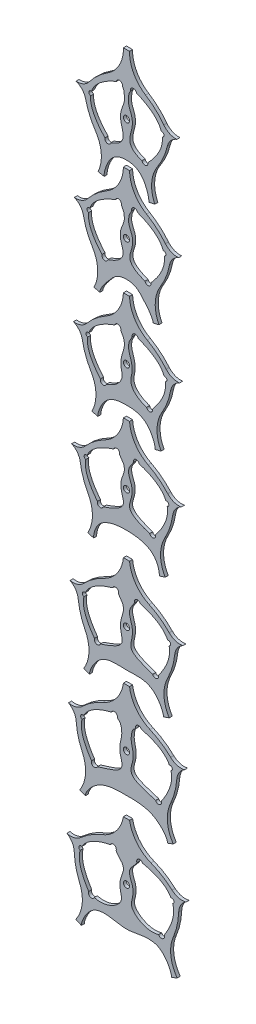
SolidWorks part; units mm, degrees
ref_plane "Front Plane" through (0, 0, 0) normal (0, 0, 1) x (1, 0, 0)
ref_plane "Top Plane" through (0, 0, 0) normal (0, 1, 0) x (1, 0, 0)
ref_plane "Right Plane" through (0, 0, 0) normal (1, 0, 0) x (0, 0, -1)
sketch "Sketch1" plane through (0, 0, 0) normal (0, 0, 1) x (1, 0, 0)
  line L0 (112.8027, 2.1803) -> (107.8321, 1.1314)
  line L1 (86.7726, 101.4585) -> (91.8526, 101.4585)
  line L2 (118.2938, 57.0694) -> (118.2268, 57.0566)
  line L3 (91.8526, 101.4585) -> (112.8027, 2.1803) construction
  line L4 (92.6064, 73.4013) -> (97.5769, 74.4502) construction
  line L5 (102.1555, 28.1498) -> (107.1261, 29.1987) construction
  line L6 (91.8526, 15.9076) -> (116.2488, -82.5805) construction
  line L7 (104.7033, -56.9977) -> (109.6343, -55.7762) construction
  line L8 (116.2488, -82.5805) -> (111.3178, -83.8019)
  line L9 (89.3126, 15.9076) -> (89.3126, -63.4628) construction
  line L10 (93.5834, -12.1064) -> (98.5144, -10.8849) construction
  line L11 (89.3126, 101.4585) -> (89.3126, 22.0881) construction
  line L12 (119.8242, -27.5334) -> (119.7577, -27.5485)
  line L13 (86.7726, 15.9076) -> (91.8526, 15.9076)
  line L14 (91.8526, -74.3544) -> (117.9639, -172.4017) construction
  line L15 (105.9737, -147.0243) -> (110.8826, -145.717) construction
  line L16 (117.9639, -172.4017) -> (113.055, -173.709)
  line L17 (89.3126, -74.3544) -> (89.3126, -153.7248) construction
  line L18 (94.0721, -102.3339) -> (98.981, -101.0266) construction
  line L19 (120.5781, -117.3006) -> (120.5119, -117.3169)
  line L20 (86.7726, -74.3544) -> (91.8526, -74.3544)
  line L21 (91.8526, -164.1408) -> (121.364, -261.2188) construction
  line L22 (108.497, -236.2745) -> (113.3573, -234.797) construction
  line L23 (121.364, -261.2188) -> (116.5036, -262.6963)
  line L24 (89.3126, -164.1408) -> (89.3126, -243.5112) construction
  line L25 (95.0455, -192.0259) -> (99.9059, -190.5484) construction
  line L26 (122.0569, -206.0601) -> (121.9913, -206.0787)
  line L27 (86.7726, -164.1408) -> (91.8526, -164.1408)
  line L28 (91.8526, -264.4679) -> (124.7283, -360.4588) construction
  line L29 (111, -335.978) -> (115.8059, -334.332) construction
  line L30 (124.7283, -360.4588) -> (119.9223, -362.1048)
  line L31 (89.3126, -264.4679) -> (89.3126, -343.8383) construction
  line L32 (96.0151, -292.2248) -> (100.821, -290.5789) construction
  line L33 (123.499, -305.3094) -> (123.4341, -305.3303)
  line L34 (86.7726, -264.4679) -> (91.8526, -264.4679)
  line L35 (91.8526, -354.4743) -> (128.0583, -449.2594) construction
  line L36 (113.484, -425.2726) -> (118.2296, -423.4599) construction
  line L37 (128.0583, -449.2594) -> (123.3127, -451.0721)
  line L38 (89.3126, -354.4743) -> (89.3126, -433.8447) construction
  line L39 (96.9813, -382.0691) -> (101.7268, -380.2564) construction
  line L40 (124.9051, -394.1865) -> (124.841, -394.2096)
  line L41 (86.7726, -354.4743) -> (91.8526, -354.4743)
  line L42 (91.8526, -450.3479) -> (131.3498, -543.8093) construction
  line L43 (115.9458, -520.3466) -> (120.6251, -518.3692) construction
  line L44 (131.3498, -543.8093) -> (126.6704, -545.7868)
  line L45 (89.3126, -450.3479) -> (89.3126, -529.7183) construction
  line L46 (97.9428, -477.7465) -> (102.6221, -475.769) construction
  line L47 (126.2732, -488.8803) -> (126.2099, -488.9057)
  line L48 (86.7726, -450.3479) -> (91.8526, -450.3479)
  line L49 (80.6823, -477.7465) -> (76.003, -475.769) construction
  line L50 (62.6793, -520.3466) -> (58, -518.3692) construction
  line L51 (86.7726, -450.3479) -> (47.2754, -543.8093) construction
  line L52 (81.6439, -382.0691) -> (76.8983, -380.2564) construction
  line L53 (65.1411, -425.2726) -> (60.3956, -423.4599) construction
  line L54 (86.7726, -354.4743) -> (50.5669, -449.2594) construction
  line L55 (82.61, -292.2248) -> (77.8041, -290.5789) construction
  line L56 (67.6251, -335.978) -> (62.8192, -334.332) construction
  line L57 (86.7726, -264.4679) -> (53.8969, -360.4588) construction
  line L58 (83.5796, -192.0259) -> (78.7192, -190.5484) construction
  line L59 (70.1282, -236.2745) -> (65.2678, -234.797) construction
  line L60 (86.7726, -164.1408) -> (57.2611, -261.2188) construction
  line L61 (84.5531, -102.3339) -> (79.6442, -101.0266) construction
  line L62 (72.6514, -147.0243) -> (67.7425, -145.717) construction
  line L63 (86.7726, -74.3544) -> (60.6612, -172.4017) construction
  line L64 (85.0417, -12.1064) -> (80.1107, -10.8849) construction
  line L65 (73.9218, -56.9977) -> (68.9908, -55.7762) construction
  line L66 (86.7726, 15.9076) -> (62.3764, -82.5805) construction
  line L67 (76.4696, 28.1498) -> (71.4991, 29.1987) construction
  line L68 (86.0188, 73.4013) -> (81.0482, 74.4502) construction
  line L69 (86.7726, 101.4585) -> (65.8225, 2.1803) construction
  line L70 (52.3519, -488.8803) -> (52.4152, -488.9057)
  line L71 (47.2754, -543.8093) -> (51.9547, -545.7868)
  line L72 (53.72, -394.1865) -> (53.7842, -394.2096)
  line L73 (50.5669, -449.2594) -> (55.3124, -451.0721)
  line L74 (55.1261, -305.3094) -> (55.191, -305.3303)
  line L75 (53.8969, -360.4588) -> (58.7028, -362.1048)
  line L76 (56.5682, -206.0601) -> (56.6338, -206.0787)
  line L77 (57.2611, -261.2188) -> (62.1215, -262.6963)
  line L78 (58.047, -117.3006) -> (58.1132, -117.3169)
  line L79 (60.6612, -172.4017) -> (65.5701, -173.709)
  line L80 (58.8009, -27.5334) -> (58.8674, -27.5485)
  line L81 (62.3764, -82.5805) -> (67.3073, -83.8019)
  line L82 (60.3314, 57.0694) -> (60.3983, 57.0566)
  line L83 (65.8225, 2.1803) -> (70.793, 1.1314)
  arc A0 (97.5769, 74.4502) -> (92.6064, 73.4013) centre (95.0916, 73.9257) ccw
  arc A1 (107.1261, 29.1987) -> (102.1555, 28.1498) centre (104.6408, 28.6742) cw
  circle A2 centre (89.3126, 51.5463) radius 2.54
  circle A3 centre (89.3126, -34.0046) radius 2.54
  arc A4 (109.6343, -55.7762) -> (104.7033, -56.9977) centre (107.1688, -56.387) cw
  arc A5 (98.5144, -10.8849) -> (93.5834, -12.1064) centre (96.0489, -11.4957) ccw
  circle A6 centre (89.3126, -124.2666) radius 2.54
  arc A7 (110.8826, -145.717) -> (105.9737, -147.0243) centre (108.4282, -146.3706) cw
  arc A8 (98.981, -101.0266) -> (94.0721, -102.3339) centre (96.5265, -101.6802) ccw
  circle A9 centre (89.3126, -214.0529) radius 2.54
  arc A10 (113.3573, -234.797) -> (108.497, -236.2745) centre (110.9272, -235.5358) cw
  arc A11 (99.9059, -190.5484) -> (95.0455, -192.0259) centre (97.4757, -191.2871) ccw
  circle A12 centre (89.3126, -312.7279) radius 2.54
  arc A13 (115.8059, -334.332) -> (111, -335.978) centre (113.403, -335.155) cw
  arc A14 (100.821, -290.5789) -> (96.0151, -292.2248) centre (98.4181, -291.4019) ccw
  circle A15 centre (89.3126, -401.8464) radius 2.54
  arc A16 (118.2296, -423.4599) -> (113.484, -425.2726) centre (115.8568, -424.3662) cw
  arc A17 (101.7268, -380.2564) -> (96.9813, -382.0691) centre (99.3541, -381.1627) ccw
  circle A18 centre (89.3126, -497.72) radius 2.54
  arc A19 (120.6251, -518.3692) -> (115.9458, -520.3466) centre (118.2855, -519.3579) cw
  arc A20 (102.6221, -475.769) -> (97.9428, -477.7465) centre (100.2825, -476.7577) ccw
  arc A21 (76.003, -475.769) -> (80.6823, -477.7465) centre (78.3427, -476.7577) cw
  arc A22 (58, -518.3692) -> (62.6793, -520.3466) centre (60.3397, -519.3579) ccw
  arc A23 (76.8983, -380.2564) -> (81.6439, -382.0691) centre (79.2711, -381.1627) cw
  arc A24 (60.3956, -423.4599) -> (65.1411, -425.2726) centre (62.7684, -424.3662) ccw
  arc A25 (77.8041, -290.5789) -> (82.61, -292.2248) centre (80.2071, -291.4019) cw
  arc A26 (62.8192, -334.332) -> (67.6251, -335.978) centre (65.2222, -335.155) ccw
  arc A27 (78.7192, -190.5484) -> (83.5796, -192.0259) centre (81.1494, -191.2871) cw
  arc A28 (65.2678, -234.797) -> (70.1282, -236.2745) centre (67.698, -235.5358) ccw
  arc A29 (79.6442, -101.0266) -> (84.5531, -102.3339) centre (82.0986, -101.6802) cw
  arc A30 (67.7425, -145.717) -> (72.6514, -147.0243) centre (70.1969, -146.3706) ccw
  arc A31 (80.1107, -10.8849) -> (85.0417, -12.1064) centre (82.5762, -11.4957) cw
  arc A32 (68.9908, -55.7762) -> (73.9218, -56.9977) centre (71.4563, -56.387) ccw
  arc A33 (71.4991, 29.1987) -> (76.4696, 28.1498) centre (73.9843, 28.6742) ccw
  arc A34 (81.0482, 74.4502) -> (86.0188, 73.4013) centre (83.5335, 73.9257) cw
  spline S0 degree 3 poles (92.6064, 73.4013) (90.7172, 69.8758) (91.4007, 69.3427) (90.6032, 59.9362) (96.814, 54.676) (90.7892, 37.3434) (93.5122, 31.002) (102.1555, 28.1498) knots 0 0 0 0 0.293254 0.369172 0.759179 0.846962 1 1 1 1
  spline S1 degree 3 poles (107.8321, 1.1314) (108.105, 3.9211) (104.5336, 16.6488) (96.4099, 22.2747) (89.3126, 22.0881) knots 0 0 0 0 0.457136 1 1 1 1
  spline S2 degree 3 poles (93.5834, -12.1064) (91.6943, -15.6318) (91.3365, -16.2096) (90.6706, -25.6141) (97.4795, -30.7687) (90.1705, -48.3057) (96.06, -54.1455) (104.7033, -56.9977) knots 0 0 0 0 0.293254 0.369172 0.759179 0.846962 1 1 1 1
  spline S3 degree 3 poles (111.3178, -83.8019) (111.5906, -81.0122) (102.464, -69.2688) (96.4099, -63.2763) (89.3126, -63.4628) knots 0 0 0 0 0.457136 1 1 1 1
  spline S4 degree 3 poles (94.0721, -102.3339) (92.1829, -105.8593) (91.2696, -106.5128) (90.7601, -115.8113) (95.9971, -123.0387) (91.5348, -136.7164) (97.3305, -144.1721) (105.9737, -147.0243) knots 0 0 0 0 0.293254 0.369172 0.759179 0.846962 1 1 1 1
  spline S5 degree 3 poles (113.055, -173.709) (113.3278, -170.9193) (107.9556, -156.16) (96.4099, -153.5383) (89.3126, -153.7248) knots 0 0 0 0 0.457136 1 1 1 1
  spline S6 degree 3 poles (95.0455, -192.0259) (93.1564, -195.5514) (91.208, -196.2555) (90.8234, -205.671) (96.7865, -210.1618) (89.6133, -228.6395) (99.8537, -233.4224) (108.497, -236.2745) knots 0 0 0 0 0.293254 0.369172 0.759179 0.846962 1 1 1 1
  spline S7 degree 3 poles (116.5036, -262.6963) (116.7765, -259.9066) (113.5664, -245.8994) (96.4099, -243.3246) (89.3126, -243.5112) knots 0 0 0 0 0.457136 1 1 1 1
  spline S8 degree 3 poles (96.0151, -292.2248) (94.126, -295.7503) (91.9511, -296.9994) (91.6538, -306.3232) (96.459, -311.0004) (91.0565, -328.7947) (102.3567, -333.1258) (111, -335.978) knots 0 0 0 0 0.293254 0.369172 0.759179 0.846962 1 1 1 1
  spline S9 degree 3 poles (119.9223, -362.1048) (120.1952, -359.3151) (111.6832, -341.6533) (96.4099, -343.6517) (89.3126, -343.8383) knots 0 0 0 0 0.457136 1 1 1 1
  spline S10 degree 3 poles (96.9813, -382.0691) (94.2417, -383.3935) (93.4077, -386.9113) (92.9499, -395.2796) (96.3902, -401.2054) (93.0624, -411.2622) (92.3782, -419.5654) (104.8407, -422.4204) (113.484, -425.2726) knots 0 0 0 0 0.280226 0.352772 0.684044 0.73546 0.825529 1 1 1 1
  spline S11 degree 3 poles (123.3127, -451.0721) (123.5855, -448.2824) (113.3022, -433.8997) (96.4099, -433.6581) (89.3126, -433.8447) knots 0 0 0 0 0.457136 1 1 1 1
  spline S12 degree 3 poles (97.9428, -477.7465) (96.0537, -481.2719) (91.8104, -483.5573) (91.8093, -492.7348) (97.0417, -497.1538) (91.4592, -514.3324) (106.7575, -523.1596) (115.9458, -520.3466) knots 0 0 0 0 0.293254 0.369172 0.759179 0.846962 1 1 1 1
  spline S13 degree 3 poles (126.6704, -545.7868) (126.9433, -542.9971) (117.5696, -521.1447) (96.5803, -529.8343) (89.3126, -529.7183) knots 0 0 0 0 0.457136 1 1 1 1
  spline S14 degree 3 poles (51.9547, -545.7868) (51.6818, -542.9971) (61.0556, -521.1447) (82.0448, -529.8343) (89.3126, -529.7183) knots 0 0 0 0 0.457136 1 1 1 1
  spline S15 degree 3 poles (80.6823, -477.7465) (82.5714, -481.2719) (86.8147, -483.5573) (86.8159, -492.7348) (81.5834, -497.1538) (87.1659, -514.3324) (71.8676, -523.1596) (62.6793, -520.3466) knots 0 0 0 0 0.293254 0.369172 0.759179 0.846962 1 1 1 1
  spline S16 degree 3 poles (55.3124, -451.0721) (55.0396, -448.2824) (65.323, -433.8997) (82.2152, -433.6581) (89.3126, -433.8447) knots 0 0 0 0 0.457136 1 1 1 1
  spline S17 degree 3 poles (81.6439, -382.0691) (84.3834, -383.3935) (85.2174, -386.9113) (85.6752, -395.2796) (82.2349, -401.2054) (85.5628, -411.2622) (86.2469, -419.5654) (73.7844, -422.4204) (65.1411, -425.2726) knots 0 0 0 0 0.280226 0.352772 0.684044 0.73546 0.825529 1 1 1 1
  spline S18 degree 3 poles (58.7028, -362.1048) (58.43, -359.3151) (66.9419, -341.6533) (82.2152, -343.6517) (89.3126, -343.8383) knots 0 0 0 0 0.457136 1 1 1 1
  spline S19 degree 3 poles (82.61, -292.2248) (84.4992, -295.7503) (86.674, -296.9994) (86.9713, -306.3232) (82.1661, -311.0004) (87.5686, -328.7947) (76.2684, -333.1258) (67.6251, -335.978) knots 0 0 0 0 0.293254 0.369172 0.759179 0.846962 1 1 1 1
  spline S20 degree 3 poles (62.1215, -262.6963) (61.8487, -259.9066) (65.0588, -245.8994) (82.2152, -243.3246) (89.3126, -243.5112) knots 0 0 0 0 0.457136 1 1 1 1
  spline S21 degree 3 poles (83.5796, -192.0259) (85.4687, -195.5514) (87.4171, -196.2555) (87.8017, -205.671) (81.8386, -210.1618) (89.0118, -228.6395) (78.7714, -233.4224) (70.1282, -236.2745) knots 0 0 0 0 0.293254 0.369172 0.759179 0.846962 1 1 1 1
  spline S22 degree 3 poles (65.5701, -173.709) (65.2973, -170.9193) (70.6696, -156.16) (82.2152, -153.5383) (89.3126, -153.7248) knots 0 0 0 0 0.457136 1 1 1 1
  spline S23 degree 3 poles (84.5531, -102.3339) (86.4422, -105.8593) (87.3556, -106.5128) (87.865, -115.8113) (82.6281, -123.0387) (87.0903, -136.7164) (81.2947, -144.1721) (72.6514, -147.0243) knots 0 0 0 0 0.293254 0.369172 0.759179 0.846962 1 1 1 1
  spline S24 degree 3 poles (67.3073, -83.8019) (67.0345, -81.0122) (76.1612, -69.2688) (82.2152, -63.2763) (89.3126, -63.4628) knots 0 0 0 0 0.457136 1 1 1 1
  spline S25 degree 3 poles (85.0417, -12.1064) (86.9308, -15.6318) (87.2886, -16.2096) (87.9545, -25.6141) (81.1456, -30.7687) (88.4547, -48.3057) (82.5651, -54.1455) (73.9218, -56.9977) knots 0 0 0 0 0.293254 0.369172 0.759179 0.846962 1 1 1 1
  spline S26 degree 3 poles (70.793, 1.1314) (70.5202, 3.9211) (74.0915, 16.6488) (82.2152, 22.2747) (89.3126, 22.0881) knots 0 0 0 0 0.457136 1 1 1 1
  spline S27 degree 3 poles (86.0188, 73.4013) (87.9079, 69.8758) (87.2244, 69.3427) (88.0219, 59.9362) (81.8112, 54.676) (87.8359, 37.3434) (85.1129, 31.002) (76.4696, 28.1498) knots 0 0 0 0 0.293254 0.369172 0.759179 0.846962 1 1 1 1
  arc B0 (91.8526, 101.4585) -> (105.1551, 76.7288) centre (120.3388, 100.8391) ccw
  arc B1 (105.1551, 76.7288) -> (120.2414, 62.8339) centre (75.0099, 28.8613) cw
  arc B2 (120.2414, 62.8339) -> (131.0703, 57.8848) centre (130.2081, 70.3198) ccw
  arc B3 (114.9788, 30.1764) -> (123.1645, 48.9822) centre (68.0628, 61.7822) ccw
  arc B4 (123.1645, 48.9822) -> (131.0703, 57.8848) centre (135.306, 46.1617) cw
  arc B5 (112.8027, 2.1803) -> (114.9788, 30.1764) centre (138.6098, 14.2569) cw
  arc B6 (118.9872, 53.4529) -> (118.2938, 57.0694) centre (118.607, 55.2547) ccw
  spline B7 degree 2 poles (118.2268, 57.0566) (114.9508, 67.1947) (97.5769, 74.4502) knots 0 0 0 1 1 1
  spline B8 degree 2 poles (118.9872, 53.4529) (120.0869, 42.8556) (107.1261, 29.1987) knots 0 0 0 1 1 1
  arc B9 (91.8526, 15.9076) -> (106.0086, -8.3437) centre (120.3431, 16.281) ccw
  arc B10 (106.0086, -8.3437) -> (121.5699, -21.7045) centre (77.5494, -57.2324) cw
  arc B11 (121.5699, -21.7045) -> (132.5646, -26.2733) centre (131.2697, -13.876) ccw
  arc B12 (117.4482, -54.5256) -> (124.9737, -35.446) centre (69.4596, -24.5735) ccw
  arc B13 (124.9737, -35.446) -> (132.5646, -26.2733) centre (137.2062, -37.8417) cw
  arc B14 (116.2488, -82.5805) -> (117.4482, -54.5256) centre (141.6195, -69.612) cw
  arc B15 (120.6433, -31.1235) -> (119.8242, -27.5334) centre (120.2005, -29.336) ccw
  spline B16 degree 2 poles (119.7577, -27.5485) (116.1305, -17.5307) (98.5144, -10.8849) knots 0 0 0 1 1 1
  spline B17 degree 2 poles (120.6433, -31.1235) (122.1115, -41.6761) (109.6343, -55.7762) knots 0 0 0 1 1 1
  arc B18 (91.8526, -74.3544) -> (106.4297, -98.3549) centre (120.3323, -73.4839) ccw
  arc B19 (106.4297, -98.3549) -> (122.2218, -111.4421) centre (78.8281, -147.7329) cw
  arc B20 (122.2218, -111.4421) -> (133.2945, -115.8184) centre (131.7835, -103.4455) ccw
  arc B21 (118.6735, -144.3301) -> (125.8649, -125.1221) centre (70.1695, -115.2202) ccw
  arc B22 (125.8649, -125.1221) -> (133.2945, -115.8184) centre (138.1373, -127.304) cw
  arc B23 (117.9639, -172.4017) -> (118.6735, -144.3301) centre (143.1044, -158.9925) cw
  arc B24 (121.4597, -120.8759) -> (120.5781, -117.3006) centre (120.9858, -119.0964) ccw
  spline B25 degree 2 poles (120.5119, -117.3169) (116.7104, -107.3639) (98.981, -101.0266) knots 0 0 0 1 1 1
  spline B26 degree 2 poles (121.4597, -120.8759) (123.1119, -131.4012) (110.8826, -145.717) knots 0 0 0 1 1 1
  arc B27 (91.8526, -164.1408) -> (107.257, -187.6188) centre (120.2846, -162.2785) ccw
  arc B28 (107.257, -187.6188) -> (123.4955, -200.1479) centre (81.3925, -237.9284) cw
  arc B29 (123.4955, -200.1479) -> (134.714, -204.1357) centre (132.7728, -191.823) ccw
  arc B30 (121.0952, -233.1396) -> (127.613, -213.6927) centre (71.6064, -205.7371) ccw
  arc B31 (127.613, -213.6927) -> (134.714, -204.1357) centre (139.954, -215.4456) cw
  arc B32 (121.364, -261.2188) -> (121.0952, -233.1396) centre (146.0221, -246.9418) cw
  arc B33 (123.0625, -209.6024) -> (122.0569, -206.0601) centre (122.5269, -207.8406) ccw
  spline B34 degree 2 poles (121.9913, -206.0787) (117.8454, -196.2642) (99.9059, -190.5484) knots 0 0 0 1 1 1
  spline B35 degree 2 poles (123.0625, -209.6024) (125.0804, -220.0639) (113.3573, -234.797) knots 0 0 0 1 1 1
  arc B36 (91.8526, -264.4679) -> (108.0656, -287.395) centre (120.2025, -261.6162) ccw
  arc B37 (108.0656, -287.395) -> (124.7307, -299.3507) centre (83.9696, -338.5752) cw
  arc B38 (124.7307, -299.3507) -> (136.0814, -302.9453) centre (133.7124, -290.7076) ccw
  arc B39 (123.4813, -332.406) -> (129.3177, -312.7438) centre (73.0679, -306.7443) ccw
  arc B40 (129.3177, -312.7438) -> (136.0814, -302.9453) centre (141.7122, -314.0658) cw
  arc B41 (124.7283, -360.4588) -> (123.4813, -332.406) centre (148.8739, -345.3314) cw
  arc B42 (124.6274, -308.8146) -> (123.499, -305.3094) centre (124.0308, -307.0724) ccw
  spline B43 degree 2 poles (123.4341, -305.3303) (118.9488, -295.6662) (100.821, -290.5789) knots 0 0 0 1 1 1
  spline B44 degree 2 poles (124.6274, -308.8146) (127.0086, -319.1994) (115.8059, -334.332) knots 0 0 0 1 1 1
  arc B45 (91.8526, -354.4743) -> (108.8559, -376.8216) centre (120.0857, -350.6349) ccw
  arc B46 (108.8559, -376.8216) -> (125.9281, -388.1884) centre (86.5607, -428.8115) cw
  arc B47 (125.9281, -388.1884) -> (137.3973, -391.3847) centre (134.6026, -379.2372) ccw
  arc B48 (125.8331, -421.2671) -> (130.9797, -401.4133) centre (74.5548, -397.3806) ccw
  arc B49 (130.9797, -401.4133) -> (137.3973, -391.3847) centre (143.4128, -402.3019) cw
  arc B50 (128.0583, -449.2594) -> (125.8331, -421.2671) centre (151.6613, -433.2985) cw
  arc B51 (126.1552, -397.6502) -> (124.9051, -394.1865) centre (125.4981, -395.9299) ccw
  spline B52 degree 2 poles (124.841, -394.2096) (120.0211, -384.7079) (101.7268, -380.2564) knots 0 0 0 1 1 1
  spline B53 degree 2 poles (126.1552, -397.6502) (128.8973, -407.9455) (118.2296, -423.4599) knots 0 0 0 1 1 1
  arc B54 (91.8526, -450.3479) -> (109.6267, -472.0871) centre (119.9342, -445.5238) ccw
  arc B55 (109.6267, -472.0871) -> (127.0859, -482.8501) centre (89.1627, -524.8247) cw
  arc B56 (127.0859, -482.8501) -> (138.6598, -485.6435) centre (135.4422, -473.6011) ccw
  arc B57 (128.1473, -515.912) -> (132.5967, -495.8903) centre (76.0653, -493.8326) ccw
  arc B58 (132.5967, -495.8903) -> (138.6598, -485.6435) centre (145.0533, -496.3437) cw
  arc B59 (131.3498, -543.8093) -> (128.1473, -515.912) centre (154.3804, -527.0331) cw
  arc B60 (127.6436, -492.2982) -> (126.2732, -488.8803) centre (126.9267, -490.6019) ccw
  spline B61 degree 2 poles (126.2099, -488.9057) (121.0608, -479.5783) (102.6221, -475.769) knots 0 0 0 1 1 1
  spline B62 degree 2 poles (127.6436, -492.2982) (130.7439, -502.4913) (120.6251, -518.3692) knots 0 0 0 1 1 1
  arc B63 (86.7726, 101.4585) -> (73.47, 76.7288) centre (58.2863, 100.8391) cw
  arc B64 (73.47, 76.7288) -> (58.3837, 62.8339) centre (103.6152, 28.8613) ccw
  arc B65 (58.3837, 62.8339) -> (47.5548, 57.8848) centre (48.417, 70.3198) cw
  arc B66 (63.6464, 30.1764) -> (55.4606, 48.9822) centre (110.5623, 61.7822) cw
  arc B67 (55.4606, 48.9822) -> (47.5548, 57.8848) centre (43.3191, 46.1617) ccw
  arc B68 (65.8225, 2.1803) -> (63.6464, 30.1764) centre (40.0154, 14.2569) ccw
  arc B69 (59.6379, 53.4529) -> (60.3314, 57.0694) centre (60.0181, 55.2547) cw
  spline B70 degree 2 poles (60.3983, 57.0566) (63.6743, 67.1947) (81.0482, 74.4502) knots 0 0 0 1 1 1
  spline B71 degree 2 poles (59.6379, 53.4529) (58.5382, 42.8556) (71.4991, 29.1987) knots 0 0 0 1 1 1
  arc B72 (86.7726, -354.4743) -> (69.7692, -376.8216) centre (58.5394, -350.6349) cw
  arc B73 (69.7692, -376.8216) -> (52.6971, -388.1884) centre (92.0644, -428.8115) ccw
  arc B74 (52.6971, -388.1884) -> (41.2279, -391.3847) centre (44.0225, -379.2372) cw
  arc B75 (52.7921, -421.2671) -> (47.6455, -401.4133) centre (104.0703, -397.3806) cw
  arc B76 (47.6455, -401.4133) -> (41.2279, -391.3847) centre (35.2124, -402.3019) ccw
  arc B77 (50.5669, -449.2594) -> (52.7921, -421.2671) centre (26.9638, -433.2985) ccw
  arc B78 (52.47, -397.6502) -> (53.72, -394.1865) centre (53.1271, -395.9299) cw
  spline B79 degree 2 poles (53.7842, -394.2096) (58.6041, -384.7079) (76.8983, -380.2564) knots 0 0 0 1 1 1
  spline B80 degree 2 poles (52.47, -397.6502) (49.7279, -407.9455) (60.3956, -423.4599) knots 0 0 0 1 1 1
  arc B81 (86.7726, -450.3479) -> (68.9984, -472.0871) centre (58.6909, -445.5238) cw
  arc B82 (68.9984, -472.0871) -> (51.5393, -482.8501) centre (89.4624, -524.8247) ccw
  arc B83 (51.5393, -482.8501) -> (39.9653, -485.6435) centre (43.183, -473.6011) cw
  arc B84 (50.4778, -515.912) -> (46.0284, -495.8903) centre (102.5598, -493.8326) cw
  arc B85 (46.0284, -495.8903) -> (39.9653, -485.6435) centre (33.5719, -496.3437) ccw
  arc B86 (47.2754, -543.8093) -> (50.4778, -515.912) centre (24.2448, -527.0331) ccw
  arc B87 (50.9815, -492.2982) -> (52.3519, -488.8803) centre (51.6984, -490.6019) cw
  spline B88 degree 2 poles (52.4152, -488.9057) (57.5644, -479.5783) (76.003, -475.769) knots 0 0 0 1 1 1
  spline B89 degree 2 poles (50.9815, -492.2982) (47.8812, -502.4913) (58, -518.3692) knots 0 0 0 1 1 1
  arc B90 (86.7726, -74.3544) -> (72.1954, -98.3549) centre (58.2929, -73.4839) cw
  arc B91 (72.1954, -98.3549) -> (56.4034, -111.4421) centre (99.797, -147.7329) ccw
  arc B92 (56.4034, -111.4421) -> (45.3306, -115.8184) centre (46.8417, -103.4455) cw
  arc B93 (59.9516, -144.3301) -> (52.7602, -125.1221) centre (108.4556, -115.2202) cw
  arc B94 (52.7602, -125.1221) -> (45.3306, -115.8184) centre (40.4878, -127.304) ccw
  arc B95 (60.6612, -172.4017) -> (59.9516, -144.3301) centre (35.5207, -158.9925) ccw
  arc B96 (57.1654, -120.8759) -> (58.047, -117.3006) centre (57.6393, -119.0964) cw
  spline B97 degree 2 poles (58.1132, -117.3169) (61.9147, -107.3639) (79.6442, -101.0266) knots 0 0 0 1 1 1
  spline B98 degree 2 poles (57.1654, -120.8759) (55.5133, -131.4012) (67.7425, -145.717) knots 0 0 0 1 1 1
  arc B99 (86.7726, 15.9076) -> (72.6165, -8.3437) centre (58.282, 16.281) cw
  arc B100 (72.6165, -8.3437) -> (57.0553, -21.7045) centre (101.0757, -57.2324) ccw
  arc B101 (57.0553, -21.7045) -> (46.0606, -26.2733) centre (47.3555, -13.876) cw
  arc B102 (61.1769, -54.5256) -> (53.6514, -35.446) centre (109.1655, -24.5735) cw
  arc B103 (53.6514, -35.446) -> (46.0606, -26.2733) centre (41.419, -37.8417) ccw
  arc B104 (62.3764, -82.5805) -> (61.1769, -54.5256) centre (37.0057, -69.612) ccw
  arc B105 (57.9819, -31.1235) -> (58.8009, -27.5334) centre (58.4246, -29.336) cw
  spline B106 degree 2 poles (58.8674, -27.5485) (62.4946, -17.5307) (80.1107, -10.8849) knots 0 0 0 1 1 1
  spline B107 degree 2 poles (57.9819, -31.1235) (56.5136, -41.6761) (68.9908, -55.7762) knots 0 0 0 1 1 1
  arc B108 (86.7726, -164.1408) -> (71.3681, -187.6188) centre (58.3405, -162.2785) cw
  arc B109 (71.3681, -187.6188) -> (55.1297, -200.1479) centre (97.2327, -237.9284) ccw
  arc B110 (55.1297, -200.1479) -> (43.9112, -204.1357) centre (45.8524, -191.823) cw
  arc B111 (57.53, -233.1396) -> (51.0121, -213.6927) centre (107.0187, -205.7371) cw
  arc B112 (51.0121, -213.6927) -> (43.9112, -204.1357) centre (38.6712, -215.4456) ccw
  arc B113 (57.2611, -261.2188) -> (57.53, -233.1396) centre (32.6031, -246.9418) ccw
  arc B114 (55.5626, -209.6024) -> (56.5682, -206.0601) centre (56.0982, -207.8406) cw
  spline B115 degree 2 poles (56.6338, -206.0787) (60.7798, -196.2642) (78.7192, -190.5484) knots 0 0 0 1 1 1
  spline B116 degree 2 poles (55.5626, -209.6024) (53.5447, -220.0639) (65.2678, -234.797) knots 0 0 0 1 1 1
  arc B117 (86.7726, -264.4679) -> (70.5595, -287.395) centre (58.4226, -261.6162) cw
  arc B118 (70.5595, -287.395) -> (53.8944, -299.3507) centre (94.6556, -338.5752) ccw
  arc B119 (53.8944, -299.3507) -> (42.5438, -302.9453) centre (44.9128, -290.7076) cw
  arc B120 (55.1438, -332.406) -> (49.3074, -312.7438) centre (105.5572, -306.7443) cw
  arc B121 (49.3074, -312.7438) -> (42.5438, -302.9453) centre (36.9129, -314.0658) ccw
  arc B122 (53.8969, -360.4588) -> (55.1438, -332.406) centre (29.7512, -345.3314) ccw
  arc B123 (53.9977, -308.8146) -> (55.1261, -305.3094) centre (54.5944, -307.0724) cw
  spline B124 degree 2 poles (55.191, -305.3303) (59.6764, -295.6662) (77.8041, -290.5789) knots 0 0 0 1 1 1
  spline B125 degree 2 poles (53.9977, -308.8146) (51.6166, -319.1994) (62.8192, -334.332) knots 0 0 0 1 1 1
  dimension "D3" = 2.54
  dimension "D2" = 5.08
  dimension "D6" = 2.54
  dimension "D7" = 2.54
  dimension "D1" = 5.08
  dimension "D4" = 2.54
  dimension "D5" = 49.9122
  dimension "D8" = 49.9122
  dimension "D9" = 5.08
  dimension "D11" = 2.54
  dimension "D13" = 5.08
  dimension "D14" = 2.54
  dimension "D16" = 49.9122
  dimension "D18" = 2.54
  dimension "D19" = 2.54
  dimension "D21" = 5.08
  dimension "D23" = 2.54
  dimension "D24" = 47.3722
  dimension "D26" = 2.54
  dimension "D28" = 47.3722
  dimension "D10" = 2.54
  dimension "D15" = 2.54
  dimension "D17" = 5.08
  dimension "D22" = 2.54
  dimension "D25" = 5.08
  dimension "D27" = 2.54
  dimension "D12" = 49.9122
  dimension "D20" = 48.26
sketch_block_instance "Block1-17"
sketch_block "Block1"
sketch_block_instance "Block1-19"
sketch_block_instance "Block1-20"
sketch_block_instance "Block1-21"
sketch_block_instance "Block1-22"
sketch_block_instance "Block1-23"
sketch_block_instance "Block1-24"
sketch_block_instance "Block1-25"
sketch_block_instance "Block1-26"
sketch_block_instance "Block1-27"
sketch_block_instance "Block1-28"
sketch_block_instance "Block1-29"
sketch_block_instance "Block1-30"
sketch_block_instance "Block1-31"
extrude "Extrude1" add sketch "Sketch1" along normal blind 2.54
